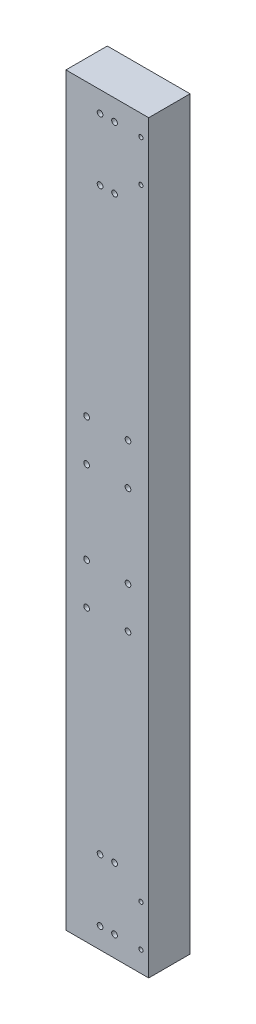
SolidWorks part; units mm, degrees
ref_plane "Front Plane" through (0, 0, 0) normal (0, 0, 1) x (1, 0, 0)
ref_plane "Top Plane" through (0, 0, 0) normal (0, 1, 0) x (1, 0, 0)
ref_plane "Right Plane" through (0, 0, 0) normal (1, 0, 0) x (0, 0, -1)
sketch "Sketch1" plane through (0, 0, 0) normal (0, 1, 0) x (1, 0, 0)
  line L1 (-50.8, 25.4) -> (50.8, 25.4)
  line L2 (-50.8, 25.4) -> (-50.8, -25.4)
  line L3 (-50.8, -25.4) -> (50.8, -25.4)
  line L4 (50.8, 25.4) -> (50.8, -25.4)
  line L5 (-50.8, 25.4) -> (50.8, -25.4) construction
  line L6 (-50.8, -25.4) -> (50.8, 25.4) construction
  point P0 (0, 0)
  dimension "D1" = 50.8
  dimension "D2" = 101.6
extrude "Boss-Extrude1" add sketch "Sketch1" along normal blind 914.4
ref_plane "Plane1" through (0, 457.2, 0) normal (0, 1, 0) x (1, 0, 0)
sketch "Sketch3" plane through (0, 0, -25.4) normal (0, 0, -1) x (-1, 0, 0)
  line L0 (-50.8, 0) -> (50.8, 0) construction
  line L1 (-8.89, 101.6) -> (8.89, 101.6) construction
  line L2 (-8.89, 101.6) -> (-8.89, 25.4) construction
  line L3 (-8.89, 25.4) -> (8.89, 25.4) construction
  line L4 (8.89, 101.6) -> (8.89, 25.4) construction
  line L5 (-8.89, 101.6) -> (8.89, 25.4) construction
  line L6 (-8.89, 25.4) -> (8.89, 101.6) construction
  circle A0 centre (-8.89, 25.4) radius 3.4925
  circle A1 centre (8.89, 25.4) radius 3.4925
  circle A2 centre (8.89, 101.6) radius 3.4925
  circle A3 centre (-8.89, 101.6) radius 3.4925
  point P0 (0, 63.5)
  dimension "D4" = 6.985
  dimension "D1" = 76.2
  dimension "D2" = 17.78
  dimension "D3" = 25.4
extrude "Cut-Extrude1" cut sketch "Sketch3" against normal up to surface (50.8 mm away) up to face at (0, 457.2, 25.4)
sketch "Sketch4" plane through (0, 0, -25.4) normal (0, 0, -1) x (-1, 0, 0)
  line L0 (-50.8, 0) -> (50.8, 0) construction
  line L1 (-50.8, 914.4) -> (-50.8, 0) construction
  circle A0 centre (-41.275, 76.2) radius 2.5527
  circle A1 centre (-41.275, 25.4) radius 2.5527
  point P4 (0, 0)
  dimension "D1" = 5.1054
  dimension "D2" = 25.4
  dimension "D3" = 50.8
  dimension "D4" = 9.525
extrude "Cut-Extrude2" cut sketch "Sketch4" against normal up to surface (50.8 mm away) up to face at (5.3975, 25.4, 25.4)
mirror "Mirror1" about plane through (0, 457.2, 0) normal (0, 1, 0) of "Cut-Extrude2", "Cut-Extrude1"
sketch "Sketch5" plane through (0, 0, -25.4) normal (0, 0, -1) x (-1, 0, 0)
  line L0 (27.94, 457.2) -> (-27.94, 457.2) construction
  line L1 (-25.4, 406.4) -> (25.4, 406.4) construction
  line L2 (-25.4, 406.4) -> (-25.4, 355.6) construction
  line L3 (-25.4, 355.6) -> (25.4, 355.6) construction
  line L4 (25.4, 406.4) -> (25.4, 355.6) construction
  line L5 (-25.4, 406.4) -> (25.4, 355.6) construction
  line L6 (-25.4, 355.6) -> (25.4, 406.4) construction
  circle A0 centre (-25.4, 406.4) radius 3.4925
  circle A1 centre (25.4, 406.4) radius 3.4925
  circle A2 centre (25.4, 355.6) radius 3.4925
  circle A3 centre (-25.4, 355.6) radius 3.4925
  point P0 (0, 381)
  dimension "D4" = 6.985
  dimension "D1" = 50.8
  dimension "D2" = 50.8
  dimension "D3" = 50.8
extrude "Cut-Extrude3" cut sketch "Sketch5" against normal up to surface (50.8 mm away) up to face at (38.7223, 838.2, 25.4)
mirror "Mirror2" about plane through (0, 457.2, 0) normal (0, 1, 0) of "Cut-Extrude3"
